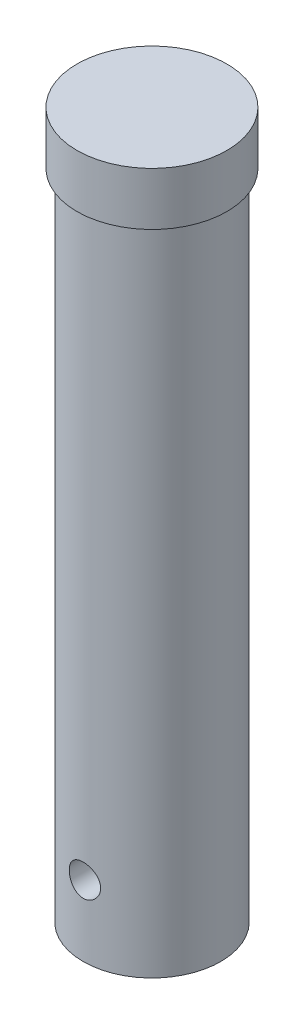
SolidWorks part; units mm, degrees
ref_plane "Front Plane" through (0, 0, 0) normal (0, 0, 1) x (1, 0, 0)
ref_plane "Top Plane" through (0, 0, 0) normal (0, 1, 0) x (1, 0, 0)
ref_plane "Right Plane" through (0, 0, 0) normal (1, 0, 0) x (0, 0, -1)
sketch "Sketch1" plane through (0, 0, 0) normal (0, 1, 0) x (1, 0, 0)
  circle A0 centre (0, 0) radius 4.953
  dimension "D1" = 9.906
extrude "Boss-Extrude1" add sketch "Sketch1" along normal blind 50.8
sketch "Sketch2" plane through (0, 50.8, 0) normal (0, 1, 0) x (1, 0, 0)
  circle A0 centre (0, 0) radius 4.953
  circle A1 centre (0, 0) radius 4.953 construction
  circle A2 centre (0, 0) radius 5.3975
  dimension "D1" = 10.795
extrude "Boss-Extrude2" add sketch "Sketch2" against normal blind 3.81
sketch "Sketch3" plane through (0, 0, 0) normal (0, 0, 1) x (1, 0, 0)
  line L0 (0, 0) -> (0, 5.08) construction
  line L1 (0, -5.9372) -> (0, 5.9372) construction
  dimension "D1" = 5.08
ref_plane "Plane1" through (0, 0, 4.953) normal (0, 0, 1) x (1, 0, 0)
hole_wizard "#4-40 Tapped Hole1" positions "Sketch4" profile "Sketch5" tap size "#4-40" standard "ANSI Inch" end condition through all
sketch "Sketch4" plane through (0, 0, 4.953) normal (0, 0, 1) x (1, 0, 0)
  point P0 (0, 5.08)
sketch "Sketch5" plane through (0, 5.08, 4.953) normal (1, 0, 0) x (0, -1, 0)
  line L0 (0, 0) -> (0, 10.3505)
  line L1 (0, 10.3505) -> (1.1303, 10.3505)
  line L2 (1.1303, 10.3505) -> (1.1303, 0)
  line L5 (1.1303, 0) -> (0, 0)
  line L11 (0, -6.35) -> (0, 107.95) construction
  dimension "Thru Tap Drill Dia." = 2.2606
  dimension "Thru Tap Drill Depth" = 10.3505
